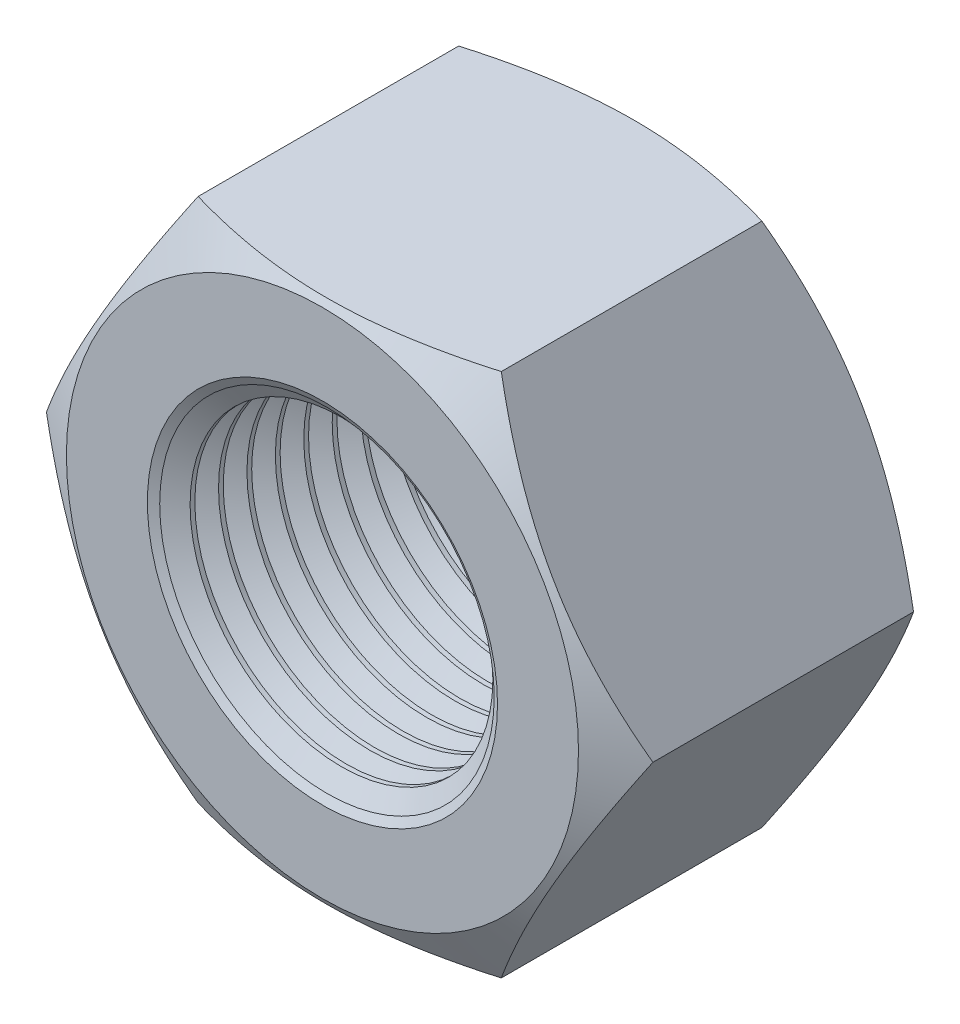
SolidWorks part; units mm, degrees
ref_plane "Front" through (0, 0, 0) normal (0, 0, 1) x (1, 0, 0)
ref_plane "Top" through (0, 0, 0) normal (0, 1, 0) x (1, 0, 0)
ref_plane "Right" through (0, 0, 0) normal (1, 0, 0) x (0, 0, -1)
sketch "Sketch1" plane through (0, 0, 0) normal (0, 0, 1) x (1, 0, 0)
  line L1 (17.3205, 0) -> (8.6603, 15)
  line L2 (8.6603, 15) -> (-8.6603, 15)
  line L3 (-8.6603, 15) -> (-17.3205, 0)
  line L4 (-17.3205, 0) -> (-8.6603, -15)
  line L5 (-8.6603, -15) -> (8.6603, -15)
  line L6 (8.6603, -15) -> (17.3205, 0)
  circle A0 centre (0, 0) radius 15 construction
  circle A1 centre (0, 0) radius 8.647
  dimension "D" = 17.294
  dimension "s" = 30
extrude "BaseNut" add sketch "Sketch1" against normal blind 18
cosmetic thread "ThreadCosmetic1" [suppressed] parameters "D"=20
sketch "Sketch2" plane through (0, 0, 0) normal (0, 1, 0) x (1, 0, 0)
  line L0 (-17.3205, 18) -> (-14.625, 18)
  line L2 (-14.625, 18) -> (-17.3205, 16.4437)
  line L3 (-17.3205, 16.4437) -> (-17.3205, 18)
  line L4 (0, 3.3759) -> (0, -9.8171) construction
  line L6 (-9.7712, 9) -> (9.8853, 9) construction
  line L7 (-17.3205, 1.5563) -> (-17.3205, 0)
  line L8 (-14.625, 0) -> (-17.3205, 1.5563)
  line L9 (-17.3205, 0) -> (-14.625, 0)
  dimension "dw" = 29.25
  dimension "D1" = 30
  dimension "D2" = 9
revolve "Double-Chamfer" cut sketch "Sketch2" angle 360 about L4
chamfer "EndChamfer" distance 1.353 angle 30 2 edges at (8.647, 0, -18) (8.647, 0, 0)
sketch "Sketch3" plane through (0, 0, 0) normal (0, 1, 0) x (1, 0, 0)
  line L0 (-9.8187, 16.647) -> (-8.647, 15.9705)
  line L1 (-8.647, 15.9705) -> (-7.294, 15.9705)
  line L2 (-7.294, 15.9705) -> (-7.294, 17.3235)
  line L3 (-7.294, 17.3235) -> (-8.647, 17.3235)
  line L4 (-8.647, 17.3235) -> (-9.8187, 16.647)
  line L5 (0, 7.4383) -> (0, 16.8806) construction
  dimension "D1" = 1.353
  dimension "D2" = 17.294
revolve "Cut-Revolve10" cut sketch "Sketch3" angle 360 about L5
pattern_linear "LPattern10" count 11 spacing 1.6236 along (0, 0, 1) of "Cut-Revolve10"
equation "\"dw@Sketch2\" = \"s@Sketch1\"-0.75"
equation "\"D2@Sketch2\" = \"m@BaseNut\" / 2"
equation "\"D2@Sketch3\" = \"D@Sketch1\""
equation "\"D1@Sketch3\" =  (\"D@ThreadCosmetic1\"   - \"D@Sketch1\")  / 2"
equation "\"D3@LPattern10\" = \"D1@Sketch3\" * 1.2"
equation "\"D1@LPattern10\" = \"m@BaseNut\"/\"D3@LPattern10\""
